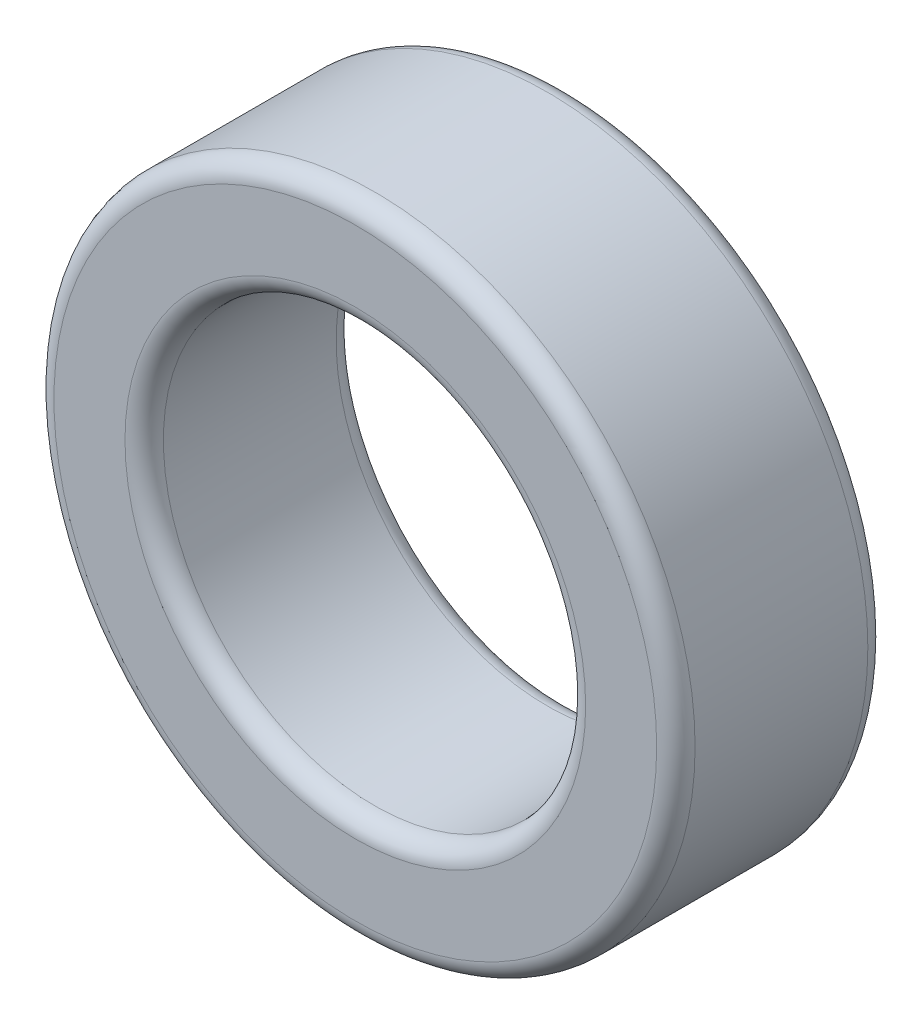
SolidWorks part; units mm, degrees
material "Polyurethane Foam Flexible"
ref_plane "Front Plane" through (0, 0, 0) normal (0, 0, 1) x (1, 0, 0)
ref_plane "Top Plane" through (0, 0, 0) normal (0, 1, 0) x (1, 0, 0)
ref_plane "Right Plane" through (0, 0, 0) normal (1, 0, 0) x (0, 0, -1)
sketch "Sketch1" plane through (0, 0, 0) normal (0, 0, 1) x (1, 0, 0)
  circle A0 centre (0, 0) radius 21.209
  circle A1 centre (0, 0) radius 13.97
  dimension "D1" = 42.418
  dimension "D2" = 27.94
extrude "Boss-Extrude1" add sketch "Sketch1" along normal blind 13.97
fillet "Fillet1" radius 1.27 4 edges at (21.209, 0, 0) (21.209, 0, 13.97) (13.97, 0, 0) (13.97, 0, 13.97)
